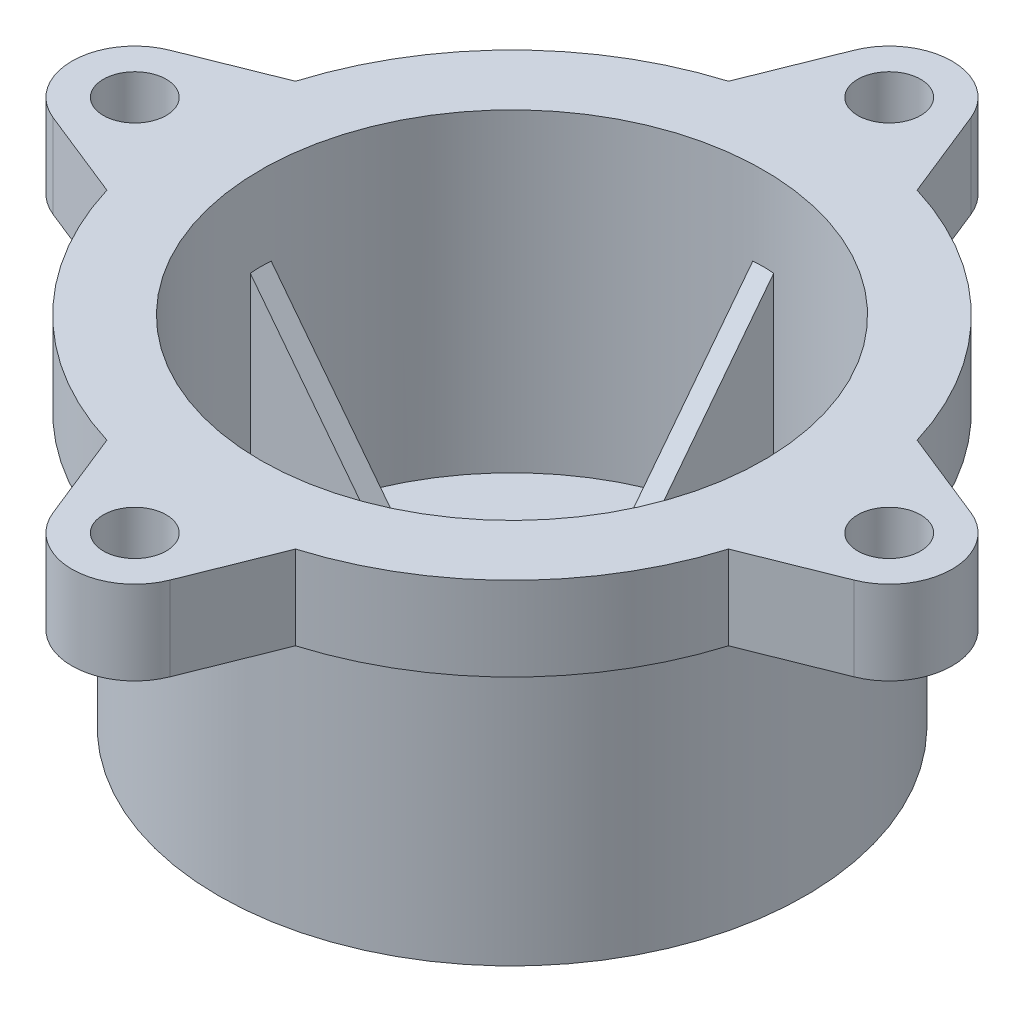
SolidWorks part; units mm, degrees
material "AISI 1035 Steel (SS)"
ref_plane "Front Plane" through (0, 0, 0) normal (0, 0, 1) x (1, 0, 0)
ref_plane "Top Plane" through (0, 0, 0) normal (0, 1, 0) x (1, 0, 0)
ref_plane "Right Plane" through (0, 0, 0) normal (1, 0, 0) x (0, 0, -1)
sketch "Sketch1" plane through (0, 0, 0) normal (0, 1, 0) x (1, 0, 0)
  circle A0 centre (0, 0) radius 12
  circle A1 centre (0, 0) radius 15.5
  dimension "D1" = 24
  dimension "D2" = 31
extrude "Boss-Extrude1" add sketch "Sketch1" along normal blind 4
sketch "Sketch2" plane through (0, 0, 0) normal (0, -1, 0) x (1, 0, 0)
  circle A0 centre (0, 0) radius 12 construction
  circle A1 centre (0, 0) radius 12
  circle A2 centre (0, 0) radius 14
  dimension "D1" = 28
extrude "Boss-Extrude2" add sketch "Sketch2" along normal blind 13
sketch "Sketch3" plane through (0, 0, 0) normal (1, 0, 0) x (0, 0, -1)
  line L0 (12, 4) -> (-12, 4) construction
  line L1 (12, 4) -> (-12, 4) construction
  line L2 (-12, -13) -> (12, -13) construction
  line L3 (-12, -13) -> (12, -13) construction
  line L4 (-12, 4) -> (-12, -13) construction
  line L5 (12, 4) -> (12, -13) construction
  line L6 (-14, 0) -> (14, 0) construction
  line L7 (-12, 0) -> (12, 0) construction
  line L8 (-12, 0) -> (-3.5, -11)
  line L9 (-3.5, -11) -> (3.5, -11)
  line L10 (3.5, -11) -> (12, 0)
  line L14 (0, 9.35) -> (0, -9.35) construction
  line L15 (-12, 0) -> (-12, -13)
  line L16 (-12, -13) -> (12, -13)
  line L17 (12, -13) -> (12, 0)
  point P8 (0, -11)
  dimension "D1" = 15
  dimension "D2" = 7
extrude "Boss-Extrude3" add sketch "Sketch3" along normal mid plane 1
pattern_circular "CirPattern1" count 4 over 360 about axis through (0, 0, 0) along (0, 1, 0) of "Boss-Extrude3"
sketch "Sketch4" plane through (0, 4, 0) normal (0, 1, 0) x (1, 0, 0)
  line L0 (0, 0) -> (0, 18) construction
  line L1 (0, -9.35) -> (0, 9.35) construction
  line L2 (-2.785, 19.1152) -> (-4.5, 14.8324)
  line L3 (2.785, 19.1152) -> (4.5, 14.8324)
  circle A0 centre (0, 18) radius 1.5
  arc A1 (2.785, 19.1152) -> (-2.785, 19.1152) centre (0, 18) ccw
  circle A3 centre (0, 0) radius 15.5 construction
  arc A4 (-4.5, 14.8324) -> (4.5, 14.8324) centre (0, 0) cw
  point P13 (0, 21)
  dimension "D3" = 6
  dimension "D5" = 3
  dimension "D6" = 15.5
  dimension "D1" = 18
  dimension "D2" = 9
  dimension "D4" = 4.5
extrude "Boss-Extrude4" add sketch "Sketch4" against normal blind 4
pattern_circular "CirPattern2" count 4 over 360 about axis through (0, 0, 0) along (0, 1, 0) of "Boss-Extrude4"
sketch "Sketch5" plane through (0, -13, 0) normal (0, -1, 0) x (1, 0, 0)
  circle A0 centre (0, 0) radius 12
  dimension "D1" = 24
extrude "Boss-Extrude5" add sketch "Sketch5" against normal blind 2
